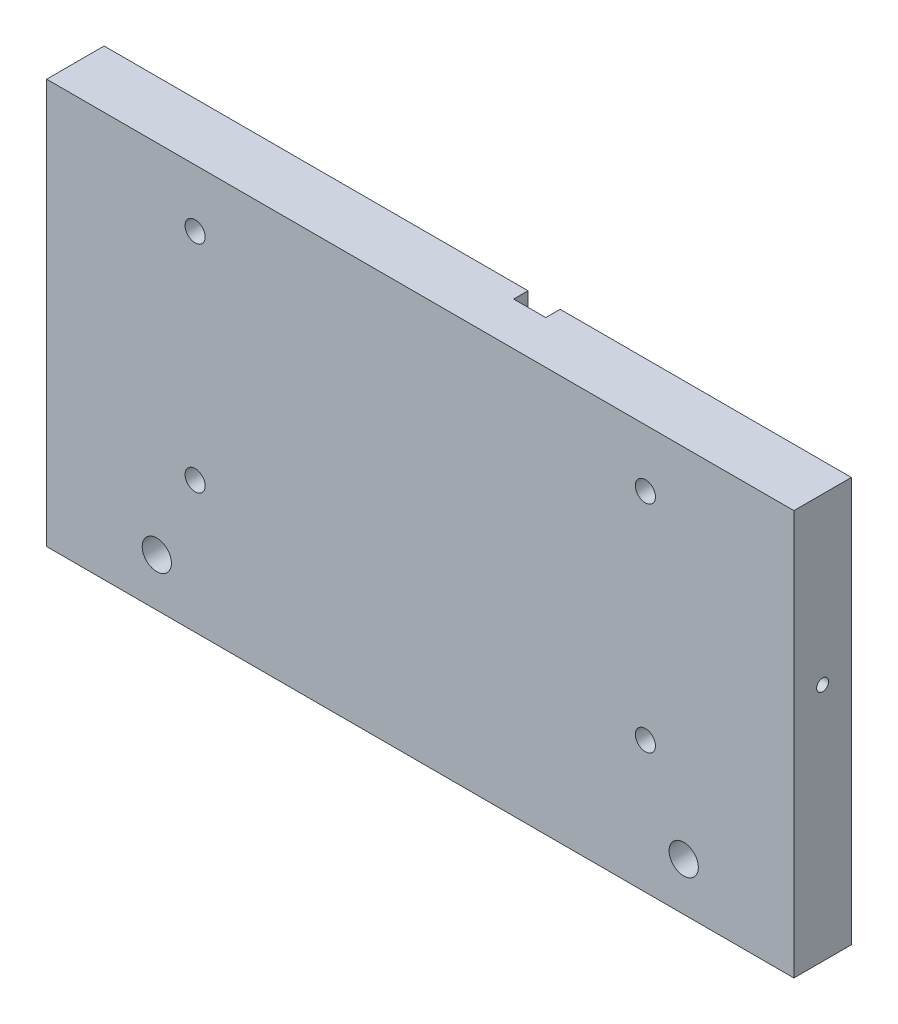
SolidWorks part; units mm, degrees
material "1.4021 (X20Cr13)"
ref_plane "Front Plane" through (0, 0, 0) normal (0, 0, 1) x (1, 0, 0)
ref_plane "Top Plane" through (0, 0, 0) normal (0, 1, 0) x (1, 0, 0)
ref_plane "Right Plane" through (0, 0, 0) normal (1, 0, 0) x (0, 0, -1)
ref_plane "Plane1" through (0, 0, 12) normal (0, 0, 1) x (1, 0, 0)
sketch "Sketch1" plane through (0, 0, 12) normal (0, 0, 1) x (1, 0, 0)
  line L0 (-78, -50) -> (78, -50)
  line L1 (78, -50) -> (78, 34.5)
  line L2 (78, 34.5) -> (-78, 34.5)
  line L3 (-78, 34.5) -> (-78, -50)
  dimension "D1" = 156
  dimension "D2" = 84.5
  dimension "D3" = 78
  dimension "D4" = 50
extrude "Boss-Extrude1" add sketch "Sketch1" against normal blind 12
sketch "Sketch2" plane through (0, 0, 0) normal (0, 0, -1) x (-1, 0, 0)
  line L0 (-10.5, 24.004) -> (-10.5, 34.5)
  line L1 (-10.5, 34.5) -> (-17.2, 34.5)
  line L2 (-17.2, 34.5) -> (-17.2, 20)
  line L3 (-17.2, 20) -> (-16.9245, 20)
  line L4 (78, 34.5) -> (78, -50) construction
  line L5 (-78, 34.5) -> (78, 34.5) construction
  arc A0 (-16.9245, 20) -> (-10.5, 24.004) centre (0, 0) ccw
  dimension "D1" = 26.2
  dimension "D2" = 78
  dimension "D3" = 88.5
  dimension "D4" = 94.9245
  dimension "D5" = 95.2
  dimension "D6" = 10.496
  dimension "D7" = 34.5
extrude "Cut-Extrude1" cut sketch "Sketch2" against normal blind 3
hole_wizard "Ø2.5 (2.5) Diameter Hole1" positions "Sketch4" profile "Sketch3" hole size "Ø2.5" standard "ANSI Metric"
sketch "Sketch4" plane through (78, 0, 0) normal (1, 0, 0) x (0, 0, -1)
  point P0 (-6, 0)
  dimension "D1" = 6
sketch "Sketch3" plane through (78, 0, 6) normal (0, 1, 0) x (0, 0, -1)
  line L0 (0, 0) -> (0, 10)
  line L1 (0, 10) -> (1.25, 10)
  line L2 (1.25, 10) -> (1.25, 0)
  line L5 (1.25, 0) -> (0, 0)
  line L10 (0, 10) -> (-1.25, 10) construction
  line L11 (0, -6.35) -> (0, 107.95) construction
  dimension "Hole Dia." = 2.5
  dimension "Hole Depth" = 10
  dimension "Drill Angle" = 180
hole_wizard "Ø6.1 (6.1) Diameter Hole1" positions "Sketch6" profile "Sketch5" hole size "Ø6.1" standard "ANSI Metric"
sketch "Sketch6" plane through (0, 0, 0) normal (0, 0, -1) x (-1, 0, 0)
  point P0 (-55, -40)
  point P1 (55, -40)
  dimension "D1" = 55
  dimension "D2" = 40
  dimension "D3" = 55
  dimension "D4" = 40
sketch "Sketch5" plane through (55, -40, 0) normal (1, 0, 0) x (0, 1, 0)
  line L0 (0, 0) -> (0, 12)
  line L1 (0, 12) -> (3.05, 12)
  line L2 (3.05, 12) -> (3.05, 0)
  line L5 (3.05, 0) -> (0, 0)
  line L11 (0, -6.35) -> (0, 107.95) construction
  dimension "Thru Hole Dia." = 6.1
  dimension "Thru Hole Depth" = 12
hole_wizard "Ø4.2 (4.2) Diameter Hole1" positions "Sketch8" profile "Sketch7" hole size "Ø4.2" standard "ANSI Metric"
sketch "Sketch8" plane through (0, 0, 12) normal (0, 0, 1) x (1, 0, 0)
  point P0 (47, 22.5)
  point P1 (-47, 22.5)
  point P2 (47, -22.5)
  point P3 (-47, -22.5)
  dimension "D1" = 47
  dimension "D2" = 22.5
  dimension "D3" = 47
  dimension "D4" = 22.5
  dimension "D5" = 47
  dimension "D6" = 22.5
  dimension "D7" = 47
  dimension "D8" = 22.5
sketch "Sketch7" plane through (47, 22.5, 12) normal (1, 0, 0) x (0, -1, 0)
  line L0 (0, 0) -> (0, 8)
  line L1 (0, 8) -> (2.1, 8)
  line L2 (2.1, 8) -> (2.1, 0)
  line L5 (2.1, 0) -> (0, 0)
  line L10 (0, 8) -> (-2.1, 8) construction
  line L11 (0, -6.35) -> (0, 107.95) construction
  dimension "Hole Dia." = 4.2
  dimension "Hole Depth" = 8
  dimension "Drill Angle" = 180
